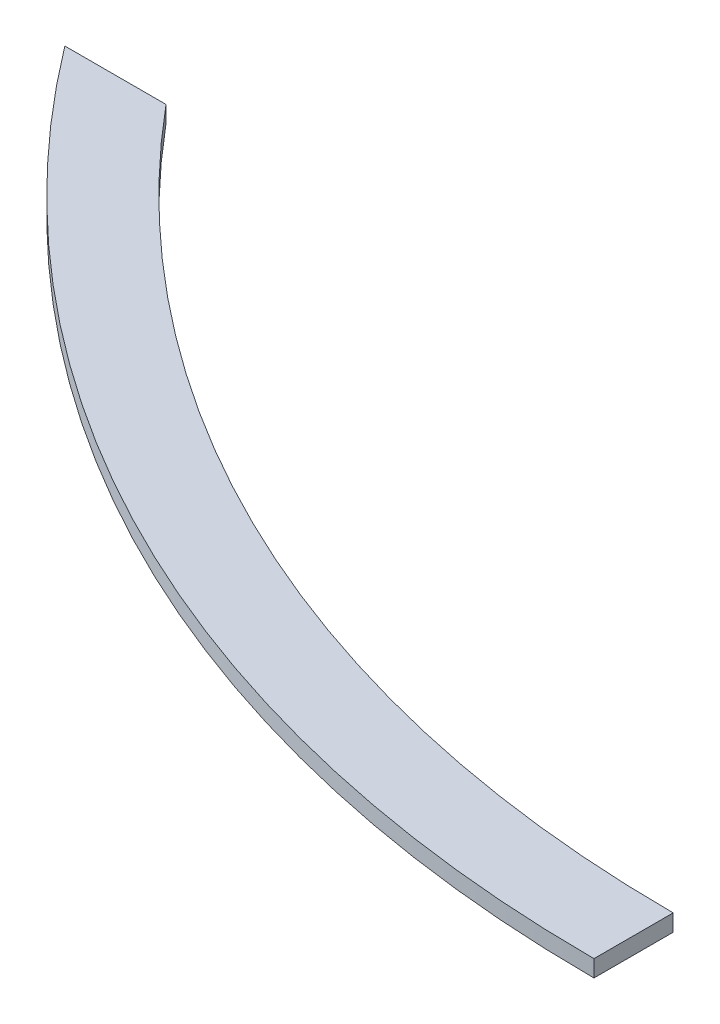
SolidWorks part; units mm, degrees
material "Pine"
ref_plane "Front Plane" through (0, 0, 0) normal (0, 0, 1) x (1, 0, 0)
ref_plane "Top Plane" through (0, 0, 0) normal (0, 1, 0) x (1, 0, 0)
ref_plane "Right Plane" through (0, 0, 0) normal (1, 0, 0) x (0, 0, -1)
sketch "Sketch2" plane through (0, 0, 0) normal (0, 1, 0) x (1, 0, 0)
  line L0 (0, 0) -> (-500, 0)
  line L1 (0, 0) -> (0, -500)
  circle A0 centre (0, 0) radius 500
  circle A1 centre (0, 0) radius 470
  dimension "D1" = 1000
  dimension "D2" = 30
extrude "Boss-Extrude1" add sketch "Sketch2" along normal blind 6.35 contours A1 L0 A0 L1
sketch "Sketch3" plane through (0, 0, 0) normal (0, 0, -1) x (-1, 0, 0)
  line L8 (470, 0) -> (500, 0)
  line L9 (500, 0) -> (500, 6.35)
  line L10 (500, 6.35) -> (470, 6.35)
  line L11 (470, 6.35) -> (470, 0)
  line L12 (470, 0) -> (500, 0)
  line L13 (500, 0) -> (500, 6.35)
  line L14 (500, 6.35) -> (470, 6.35)
  line L15 (470, 6.35) -> (470, 0)
  dimension "D1" = 0
extrude "Boss-Extrude2" add sketch "Sketch3" along normal blind 80
sketch "Sketch4" plane through (0, 6.35, 0) normal (0, 1, 0) x (1, 0, 0)
  line L1 (-500, 80) -> (0, 80) construction
  line L2 (-500, 80) -> (-500, -500) construction
  line L3 (-500, -500) -> (0, -500) construction
  line L4 (0, 80) -> (0, -500) construction
  line L5 (-500, 80) -> (-195.2, 80) construction
  line L6 (-500, 80) -> (-500, -326.4) construction
  line L7 (-500, -326.4) -> (-195.2, -326.4) construction
  line L8 (-195.2, 80) -> (-195.2, -326.4) construction
  line L9 (0, -500) -> (-406.4, -500) construction
  line L10 (0, -500) -> (0, -195.2) construction
  line L11 (0, -195.2) -> (-406.4, -195.2) construction
  line L12 (-406.4, -500) -> (-406.4, -195.2) construction
  dimension "D1" = 304.8
  dimension "D2" = 406.4
  dimension "D3" = 304.8
  dimension "D4" = 406.4
ref_plane "Plane1" through (0, 0, 301) normal (0, 0, -1) x (-1, 0, 0)
split "Split1" trim tools "Plane1" bodies to split 102 resulting bodies 103
